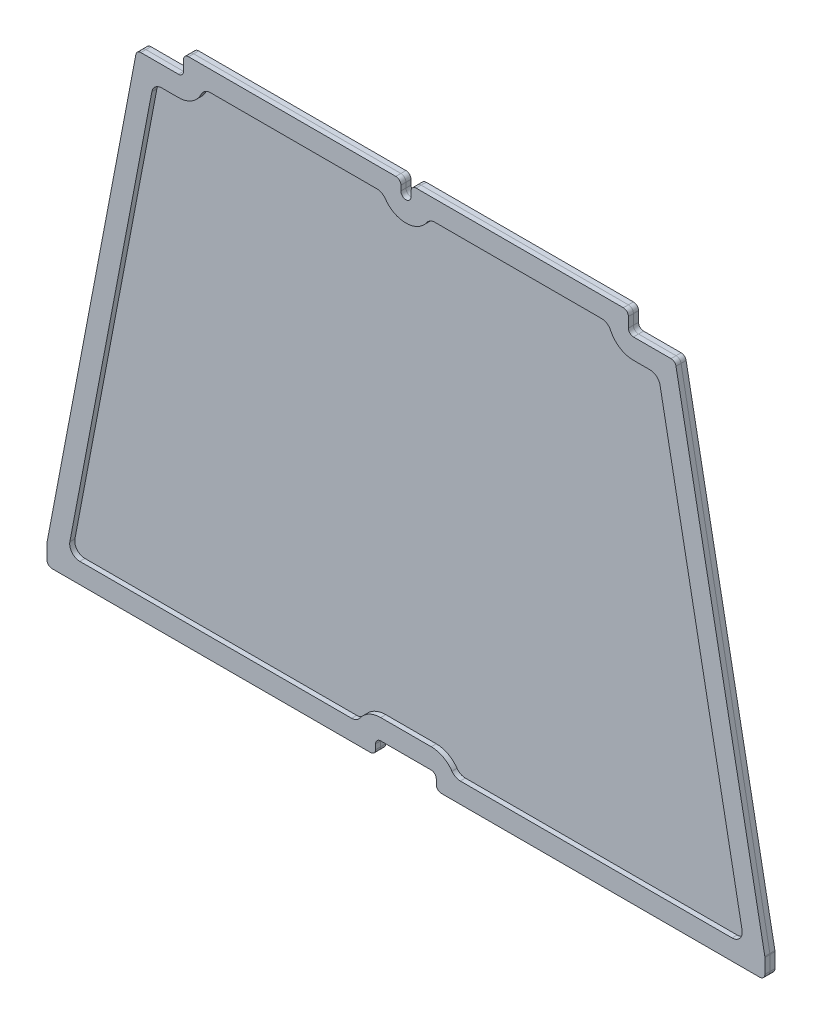
SolidWorks part; units mm, degrees
ref_plane "正面" through (0, 0, 0) normal (0, 0, 1) x (1, 0, 0)
ref_plane "平面" through (0, 0, 0) normal (0, 1, 0) x (1, 0, 0)
ref_plane "右側面" through (0, 0, 0) normal (1, 0, 0) x (0, 0, -1)
sketch "ｽｹｯﾁ2" plane through (0, 0, 0) normal (0, 0, 1) x (1, 0, 0)
  line L0 (0, 0) -> (0, 26.7695) construction
  line L1 (355, 0) -> (-355, 0)
  line L2 (-355, 0) -> (-355, 20)
  line L3 (-355, 20) -> (-262.5, 506)
  line L4 (-262.5, 506) -> (262.5, 506)
  line L5 (355, 20) -> (262.5, 506)
  line L6 (355, 0) -> (355, 20)
  point P11 (0, 506)
  point P13 (0, 0)
  dimension "D1" = 20
  dimension "D2" = 710
  dimension "D3" = 506
  dimension "D4" = 525
extrude "ﾎﾞｽ - 押し出し1" add sketch "ｽｹｯﾁ2" along normal blind 5
sketch "ｽｹｯﾁ3" plane through (0, 0, 5) normal (0, 0, 1) x (1, 0, 0)
  line L0 (-264.4033, 496) -> (264.4033, 496) construction
  line L1 (-262.5, 506) -> (-355, 20) construction
  line L2 (355, 20) -> (262.5, 506) construction
  line L3 (0, 506) -> (0, 0) construction
  line L4 (262.5, 506) -> (-262.5, 506) construction
  line L5 (-266.3066, 486) -> (-220, 486)
  line L6 (-220, 486) -> (-220, 506)
  line L7 (220, 486) -> (220, 506)
  line L8 (266.3066, 486) -> (220, 486)
  line L9 (-5, 496) -> (-5, 506)
  line L10 (5, 496) -> (5, 506)
  line L11 (-355, 20) -> (-355, 0)
  line L12 (-355, 0) -> (355, 0)
  line L13 (355, 0) -> (355, 20)
  line L14 (355, 20) -> (262.5, 506)
  line L15 (262.5, 506) -> (-262.5, 506)
  line L16 (-262.5, 506) -> (-355, 20)
  line L17 (-355, 20) -> (-355, 0)
  line L18 (-355, 0) -> (355, 0)
  line L19 (355, 0) -> (355, 20)
  line L20 (355, 20) -> (262.5, 506)
  line L21 (262.5, 506) -> (-262.5, 506)
  line L22 (-262.5, 506) -> (-355, 20)
  line L23 (0, 10) -> (25, 10) construction
  line L24 (25, 15) -> (-25, 15)
  line L25 (30, 10) -> (30, 0)
  line L26 (-30, 10) -> (-30, 0)
  line L27 (-30, 0) -> (30, 0)
  arc A0 (-220, 496) -> (-230, 496) centre (-225, 496) ccw construction
  arc A1 (-230, 496) -> (-220, 496) centre (-225, 496) ccw construction
  arc A2 (230, 496) -> (220, 496) centre (225, 496) cw construction
  arc A3 (220, 496) -> (230, 496) centre (225, 496) cw construction
  arc A4 (-5, 496) -> (5, 496) centre (0, 496) ccw
  arc A5 (0, 501) -> (-5, 496) centre (0, 496) ccw construction
  arc A6 (5, 496) -> (0, 501) centre (0, 496) ccw construction
  arc A7 (30, 10) -> (25, 15) centre (25, 10) ccw
  arc A8 (-30, 10) -> (-25, 15) centre (-25, 10) cw
  arc A9 (-25, 15) -> (-30, 10) centre (-25, 10) cw construction
  arc A10 (20, 10) -> (30, 10) centre (25, 10) ccw construction
  arc A11 (25, 15) -> (20, 10) centre (25, 10) ccw construction
  line M13 (355, 20) -> (262.5, 506)
  line M14 (262.5, 506) -> (-262.5, 506)
  line M15 (-262.5, 506) -> (-355, 20)
  dimension "D2" = 10
  dimension "D6" = 10
  dimension "D7" = 10
  dimension "D1" = 10
  dimension "D3" = 37.5
  dimension "D5" = 20
  dimension "D8" = 50
  dimension "D9" = 10
  dimension "D4" = 0
extrude "ｶｯﾄ - 押し出し1" cut sketch "ｽｹｯﾁ3" against normal through all contours L5 L6 M14 M15 | L8 L7 M13 M14 | L9 A4 L10 M14 | A8 L26 L18 L25 A7 L24
fillet "ﾌｨﾚｯﾄ1" radius 5 14 edges at (355, 20, 2.5) (-355, 20, 2.5) (-355, 0, 2.5) (355, 0, 2.5) (30, 0, 2.5) (-30, 0, 2.5) (266.3066, 486, 2.5) (220, 486, 2.5) (220, 506, 2.5) (5, 506, 2.5) (-5, 506, 2.5) (-220, 506, 2.5) (-220, 486, 2.5) (-266.3066, 486, 2.5)
sketch "ｽｹｯﾁ4" plane through (0, 0, 5) normal (0, 0, 1) x (1, 0, 0)
  line L0 (-225, 466) -> (-249.7541, 466)
  line L1 (-249.7541, 466) -> (-334.641, 20)
  line L2 (-334.641, 20) -> (-334.641, 20)
  line L3 (-334.641, 20) -> (-47.9129, 20)
  line L4 (-47.9129, 20) -> (-47.9129, 20)
  line L5 (-25, 35) -> (25, 35)
  line L6 (47.9129, 20) -> (47.9129, 20)
  line L7 (47.9129, 20) -> (334.641, 20)
  line L8 (334.641, 20) -> (334.641, 20)
  line L9 (334.641, 20) -> (249.7541, 466)
  line L10 (249.7541, 466) -> (225, 466)
  line L11 (200.5051, 486) -> (200.5051, 486)
  line L12 (200.5051, 486) -> (22.9129, 486)
  line L13 (22.9129, 486) -> (22.9129, 486)
  line L14 (-22.9129, 486) -> (-22.9129, 486)
  line L15 (-22.9129, 486) -> (-200.5051, 486)
  line L16 (-200.5051, 486) -> (-200.5051, 486)
  line L17 (30, 10) -> (30, 5)
  line L18 (35, 0) -> (350, 0)
  line L19 (355, 5) -> (355, 19.5284)
  line L20 (354.9118, 20.4633) -> (267.0803, 481.9349)
  line L21 (262.1685, 486) -> (225, 486)
  line L22 (220, 491) -> (220, 501)
  line L23 (215, 506) -> (10, 506)
  line L24 (5, 501) -> (5, 496)
  line L25 (-5, 496) -> (-5, 501)
  line L26 (-10, 506) -> (-215, 506)
  line L27 (-220, 501) -> (-220, 491)
  line L28 (-225, 486) -> (-262.1685, 486)
  line L29 (-267.0803, 481.9349) -> (-354.9118, 20.4633)
  line L30 (-355, 19.5284) -> (-355, 5)
  line L31 (-350, 0) -> (-35, 0)
  line L32 (-30, 5) -> (-30, 10)
  line L33 (-25, 15) -> (25, 15)
  line L34 (30, 10) -> (30, 5)
  line L35 (35, 0) -> (350, 0)
  line L36 (355, 5) -> (355, 19.5284)
  line L37 (354.9118, 20.4633) -> (267.0803, 481.9349)
  line L38 (262.1685, 486) -> (225, 486)
  line L39 (220, 491) -> (220, 501)
  line L40 (215, 506) -> (10, 506)
  line L41 (5, 501) -> (5, 496)
  line L42 (-5, 496) -> (-5, 501)
  line L43 (-10, 506) -> (-215, 506)
  line L44 (-220, 501) -> (-220, 491)
  line L45 (-225, 486) -> (-262.1685, 486)
  line L46 (-267.0803, 481.9349) -> (-354.9118, 20.4633)
  line L47 (-355, 19.5284) -> (-355, 5)
  line L48 (-350, 0) -> (-35, 0)
  line L49 (-30, 5) -> (-30, 10)
  line L50 (-25, 15) -> (25, 15)
  arc A0 (-249.7541, 466) -> (-249.7541, 466) centre (-249.7541, 466) ccw
  arc A1 (-334.641, 20) -> (-334.641, 20) centre (-334.641, 20) ccw
  arc A2 (-334.641, 20) -> (-334.641, 20) centre (-334.641, 20) ccw
  arc A3 (-47.9129, 20) -> (-47.9129, 20) centre (-47.9129, 20) ccw
  arc A4 (-25, 35) -> (-47.9129, 20) centre (-25, 10) ccw
  arc A5 (47.9129, 20) -> (25, 35) centre (25, 10) ccw
  arc A6 (47.9129, 20) -> (47.9129, 20) centre (47.9129, 20) ccw
  arc A7 (334.641, 20) -> (334.641, 20) centre (334.641, 20) ccw
  arc A8 (334.641, 20) -> (334.641, 20) centre (334.641, 20) ccw
  arc A9 (249.7541, 466) -> (249.7541, 466) centre (249.7541, 466) ccw
  arc A10 (200.5051, 486) -> (225, 466) centre (225, 491) ccw
  arc A11 (200.5051, 486) -> (200.5051, 486) centre (200.5051, 486) ccw
  arc A12 (22.9129, 486) -> (22.9129, 486) centre (22.9129, 486) ccw
  arc A13 (-22.9129, 486) -> (22.9129, 486) centre (0, 496) ccw
  arc A14 (-22.9129, 486) -> (-22.9129, 486) centre (-22.9129, 486) ccw
  arc A15 (-200.5051, 486) -> (-200.5051, 486) centre (-200.5051, 486) ccw
  arc A16 (-225, 466) -> (-200.5051, 486) centre (-225, 491) ccw
  arc A17 (30, 5) -> (35, 0) centre (35, 5) ccw
  arc A18 (350, 0) -> (355, 5) centre (350, 5) ccw
  arc A19 (355, 19.5284) -> (354.9118, 20.4633) centre (350, 19.5284) ccw
  arc A20 (267.0803, 481.9349) -> (262.1685, 486) centre (262.1685, 481) ccw
  arc A21 (220, 491) -> (225, 486) centre (225, 491) ccw
  arc A22 (220, 501) -> (215, 506) centre (215, 501) ccw
  arc A23 (10, 506) -> (5, 501) centre (10, 501) ccw
  arc A24 (-5, 496) -> (5, 496) centre (0, 496) ccw
  arc A25 (-5, 501) -> (-10, 506) centre (-10, 501) ccw
  arc A26 (-215, 506) -> (-220, 501) centre (-215, 501) ccw
  arc A27 (-225, 486) -> (-220, 491) centre (-225, 491) ccw
  arc A28 (-262.1685, 486) -> (-267.0803, 481.9349) centre (-262.1685, 481) ccw
  arc A29 (-354.9118, 20.4633) -> (-355, 19.5284) centre (-350, 19.5284) ccw
  arc A30 (-355, 5) -> (-350, 0) centre (-350, 5) ccw
  arc A31 (-35, 0) -> (-30, 5) centre (-35, 5) ccw
  arc A32 (-25, 15) -> (-30, 10) centre (-25, 10) ccw
  arc A33 (30, 10) -> (25, 15) centre (25, 10) ccw
  arc A34 (30, 5) -> (35, 0) centre (35, 5) ccw
  arc A35 (350, 0) -> (355, 5) centre (350, 5) ccw
  arc A36 (355, 19.5284) -> (354.9118, 20.4633) centre (350, 19.5284) ccw
  arc A37 (267.0803, 481.9349) -> (262.1685, 486) centre (262.1685, 481) ccw
  arc A38 (220, 491) -> (225, 486) centre (225, 491) ccw
  arc A39 (220, 501) -> (215, 506) centre (215, 501) ccw
  arc A40 (10, 506) -> (5, 501) centre (10, 501) ccw
  arc A41 (-5, 496) -> (5, 496) centre (0, 496) ccw
  arc A42 (-5, 501) -> (-10, 506) centre (-10, 501) ccw
  arc A43 (-215, 506) -> (-220, 501) centre (-215, 501) ccw
  arc A44 (-225, 486) -> (-220, 491) centre (-225, 491) ccw
  arc A45 (-262.1685, 486) -> (-267.0803, 481.9349) centre (-262.1685, 481) ccw
  arc A46 (-354.9118, 20.4633) -> (-355, 19.5284) centre (-350, 19.5284) ccw
  arc A47 (-355, 5) -> (-350, 0) centre (-350, 5) ccw
  arc A48 (-35, 0) -> (-30, 5) centre (-35, 5) ccw
  arc A49 (-25, 15) -> (-30, 10) centre (-25, 10) ccw
  arc A50 (30, 10) -> (25, 15) centre (25, 10) ccw
  dimension "D1" = 0
  dimension "D2" = 20
extrude "ﾎﾞｽ - 押し出し2" add sketch "ｽｹｯﾁ4" along normal blind 5 separate body
fillet "ﾌｨﾚｯﾄ2" radius 10 10 edges at (249.7541, 466, 7.5) (200.5051, 486, 7.5) (22.9129, 486, 7.5) (-22.9129, 486, 7.5) (-200.5051, 486, 7.5) (-249.7541, 466, 7.5) (-47.9129, 20, 7.5) (47.9129, 20, 7.5) (334.641, 20, 7.5) (-334.641, 20, 7.5)
sketch "ｽｹｯﾁ5" plane through (0, 0, 10) normal (0, 0, 1) x (1, 0, 0)
  line L0 (0, 491) -> (0, 15)
  line L1 (-25, 15) -> (25, 15) construction
  line L19 (30, 10) -> (30, 5)
  line L20 (35, 0) -> (350, 0)
  line L21 (355, 5) -> (355, 19.5284)
  line L22 (354.9118, 20.4633) -> (267.0803, 481.9349)
  line L23 (262.1685, 486) -> (225, 486)
  line L24 (220, 491) -> (220, 501)
  line L25 (215, 506) -> (10, 506)
  line L26 (5, 501) -> (5, 496)
  line L27 (-5, 496) -> (-5, 501)
  line L28 (-10, 506) -> (-215, 506)
  line L29 (-220, 501) -> (-220, 491)
  line L30 (-225, 486) -> (-262.1685, 486)
  line L31 (-267.0803, 481.9349) -> (-354.9118, 20.4633)
  line L32 (-355, 19.5284) -> (-355, 5)
  line L33 (-350, 0) -> (-35, 0)
  line L34 (-30, 5) -> (-30, 10)
  line L35 (-25, 15) -> (25, 15)
  line L36 (30, 10) -> (30, 5)
  line L37 (35, 0) -> (350, 0)
  line L38 (355, 5) -> (355, 19.5284)
  line L39 (354.9118, 20.4633) -> (267.0803, 481.9349)
  line L40 (262.1685, 486) -> (225, 486)
  line L41 (220, 491) -> (220, 501)
  line L42 (215, 506) -> (10, 506)
  line L43 (5, 501) -> (5, 496)
  line L44 (-5, 496) -> (-5, 501)
  line L45 (-10, 506) -> (-215, 506)
  line L46 (-220, 501) -> (-220, 491)
  line L47 (-225, 486) -> (-262.1685, 486)
  line L48 (-267.0803, 481.9349) -> (-354.9118, 20.4633)
  line L49 (-355, 19.5284) -> (-355, 5)
  line L50 (-350, 0) -> (-35, 0)
  line L51 (-30, 5) -> (-30, 10)
  line L52 (-25, 15) -> (25, 15)
  arc A0 (-5, 496) -> (5, 496) centre (0, 496) ccw construction
  arc A18 (30, 10) -> (25, 15) centre (25, 10) ccw
  arc A19 (30, 5) -> (35, 0) centre (35, 5) ccw
  arc A20 (350, 0) -> (355, 5) centre (350, 5) ccw
  arc A21 (355, 19.5284) -> (354.9118, 20.4633) centre (350, 19.5284) ccw
  arc A22 (267.0803, 481.9349) -> (262.1685, 486) centre (262.1685, 481) ccw
  arc A23 (220, 491) -> (225, 486) centre (225, 491) ccw
  arc A24 (220, 501) -> (215, 506) centre (215, 501) ccw
  arc A25 (10, 506) -> (5, 501) centre (10, 501) ccw
  arc A26 (-5, 496) -> (5, 496) centre (0, 496) ccw
  arc A27 (-5, 501) -> (-10, 506) centre (-10, 501) ccw
  arc A28 (-215, 506) -> (-220, 501) centre (-215, 501) ccw
  arc A29 (-225, 486) -> (-220, 491) centre (-225, 491) ccw
  arc A30 (-262.1685, 486) -> (-267.0803, 481.9349) centre (-262.1685, 481) ccw
  arc A31 (-354.9118, 20.4633) -> (-355, 19.5284) centre (-350, 19.5284) ccw
  arc A32 (-355, 5) -> (-350, 0) centre (-350, 5) ccw
  arc A33 (-35, 0) -> (-30, 5) centre (-35, 5) ccw
  arc A34 (-25, 15) -> (-30, 10) centre (-25, 10) ccw
  arc A35 (30, 10) -> (25, 15) centre (25, 10) ccw
  arc A36 (30, 5) -> (35, 0) centre (35, 5) ccw
  arc A37 (350, 0) -> (355, 5) centre (350, 5) ccw
  arc A38 (355, 19.5284) -> (354.9118, 20.4633) centre (350, 19.5284) ccw
  arc A39 (267.0803, 481.9349) -> (262.1685, 486) centre (262.1685, 481) ccw
  arc A40 (220, 491) -> (225, 486) centre (225, 491) ccw
  arc A41 (220, 501) -> (215, 506) centre (215, 501) ccw
  arc A42 (10, 506) -> (5, 501) centre (10, 501) ccw
  arc A43 (-5, 496) -> (5, 496) centre (0, 496) ccw
  arc A44 (-5, 501) -> (-10, 506) centre (-10, 501) ccw
  arc A45 (-215, 506) -> (-220, 501) centre (-215, 501) ccw
  arc A46 (-225, 486) -> (-220, 491) centre (-225, 491) ccw
  arc A47 (-262.1685, 486) -> (-267.0803, 481.9349) centre (-262.1685, 481) ccw
  arc A48 (-354.9118, 20.4633) -> (-355, 19.5284) centre (-350, 19.5284) ccw
  arc A49 (-355, 5) -> (-350, 0) centre (-350, 5) ccw
  arc A50 (-35, 0) -> (-30, 5) centre (-35, 5) ccw
  arc A51 (-25, 15) -> (-30, 10) centre (-25, 10) ccw
  dimension "D1" = 0
extrude "ｶｯﾄ - 押し出し2" [suppressed] cut sketch "ｽｹｯﾁ5" against normal through all contours A51 L52 L0 A43 L44 A44 L45 A45 L46 A46 L47 A47 L48 A48 L49 A49 L50 A50 L51
